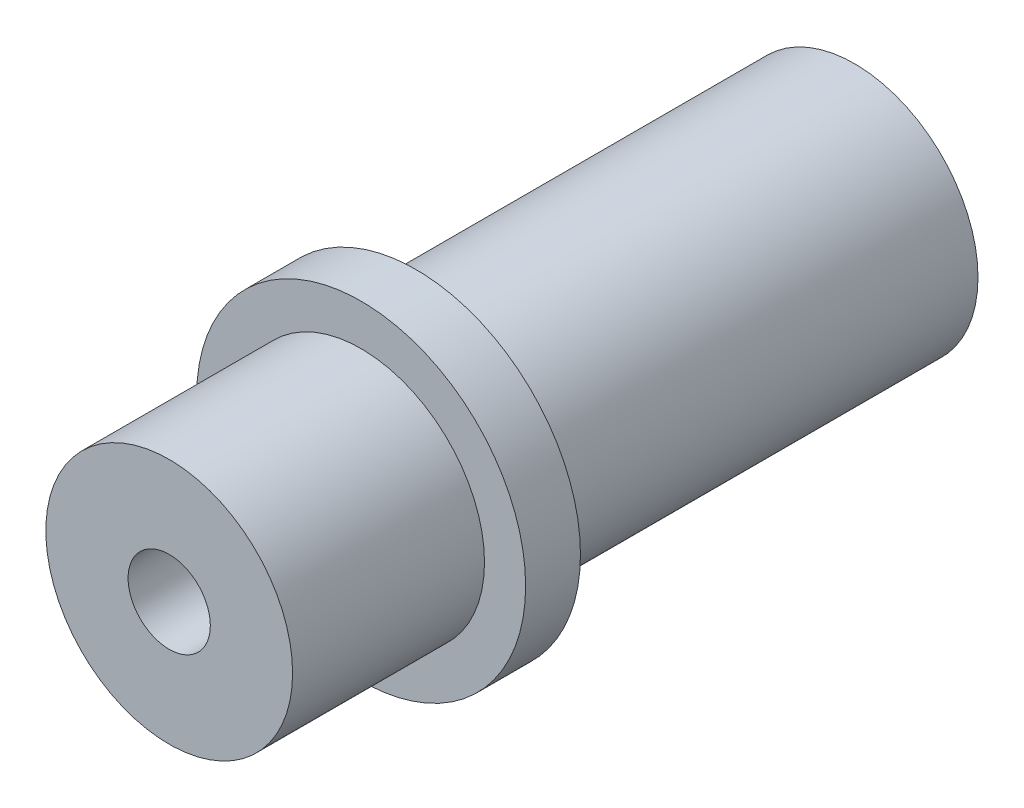
SolidWorks part; units mm, degrees
ref_plane "Ön Düzlem" through (0, 0, 0) normal (0, 0, 1) x (1, 0, 0)
ref_plane "Üst Düzlem" through (0, 0, 0) normal (0, 1, 0) x (1, 0, 0)
ref_plane "Sağ Düzlem" through (0, 0, 0) normal (1, 0, 0) x (0, 0, -1)
sketch "Çizim1" plane through (0, 0, 0) normal (1, 0, 0) x (0, 0, -1)
  line L0 (7.3657, 5.625) -> (27.3657, 5.625)
  line L1 (-3.8843, 5.625) -> (4.8657, 5.625)
  line L2 (-3.8843, 5.625) -> (-3.8843, 1.875)
  line L3 (-3.8843, 1.875) -> (27.3657, 1.875)
  line L4 (27.3657, 5.625) -> (27.3657, 1.875)
  line L5 (4.8657, 7.5) -> (7.3657, 7.5)
  line L6 (4.8657, 7.5) -> (4.8657, 5.625)
  line L8 (7.3657, 7.5) -> (7.3657, 5.625)
  line L9 (-4.3802, 0) -> (11.9421, 0) construction
  dimension "D1" = 2.5
  dimension "D2" = 20
  dimension "D3" = 31.25
  dimension "D4" = 7.5
  dimension "D5" = 5.625
  dimension "D6" = 1.875
revolve "Döndür1" add sketch "Çizim1" angle 360 about L9
